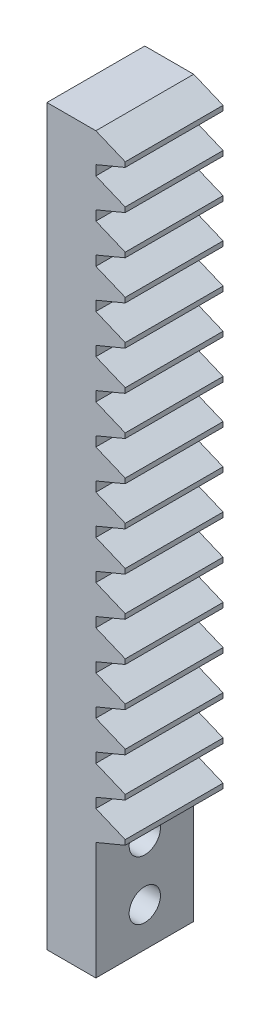
SolidWorks part; units mm, degrees
ref_plane "Plan de face" through (0, 0, 0) normal (0, 0, 1) x (1, 0, 0)
ref_plane "Plan de dessus" through (0, 0, 0) normal (0, 1, 0) x (1, 0, 0)
ref_plane "Plan de droite" through (0, 0, 0) normal (1, 0, 0) x (0, 0, -1)
sketch "Esquisse1" plane through (0, 0, 0) normal (1, 0, 0) x (0, 0, -1)
  line L0 (0, 0) -> (0, 75)
  line L1 (0, 75) -> (10, 75)
  line L2 (10, 75) -> (10, 0)
  line L3 (10, 0) -> (0, 0)
  dimension "D1" = 75
  dimension "D2" = 10
extrude "Boss.-Extru.1" add sketch "Esquisse1" against normal blind 5
sketch "Esquisse2" plane through (0, 0, 0) normal (0, 0, 1) x (1, 0, 0)
  line L0 (0, 75) -> (3, 73.75)
  line L1 (3, 73.75) -> (3, 73.25)
  line L2 (0, 75) -> (0, 0) construction
  line L3 (0, 75) -> (0, 72) construction
  line L4 (3, 73.25) -> (0, 72)
  line L5 (0, 73.5) -> (3, 73.5) construction
  line L9 (0, 0) -> (0, 75)
  line L10 (0, 75) -> (-5, 75)
  line L11 (-5, 75) -> (-5, 0)
  line L12 (-5, 0) -> (0, 0)
  line L13 (0, 72) -> (0, 75)
  dimension "D1" = 3
  dimension "D2" = 1.5
  dimension "D4" = 0.5
  dimension "D3" = 0
extrude "Boss.-Extru.2" add sketch "Esquisse2" against normal blind 10
pattern_linear "Répétition linéaire1" count 16 spacing 4 along (0, -1, 0) of "Boss.-Extru.2"
sketch "Esquisse3" plane through (0, 0, 0) normal (1, 0, 0) x (0, 0, -1)
  circle A0 centre (5, 10) radius 1.6
  circle A1 centre (5, 4) radius 1.6
  dimension "D1" = 3.2
  dimension "D2" = 5
  dimension "D3" = 10
  dimension "D4" = 4
extrude "Enlèv. mat.-Extru.1" cut sketch "Esquisse3" against normal blind 10
